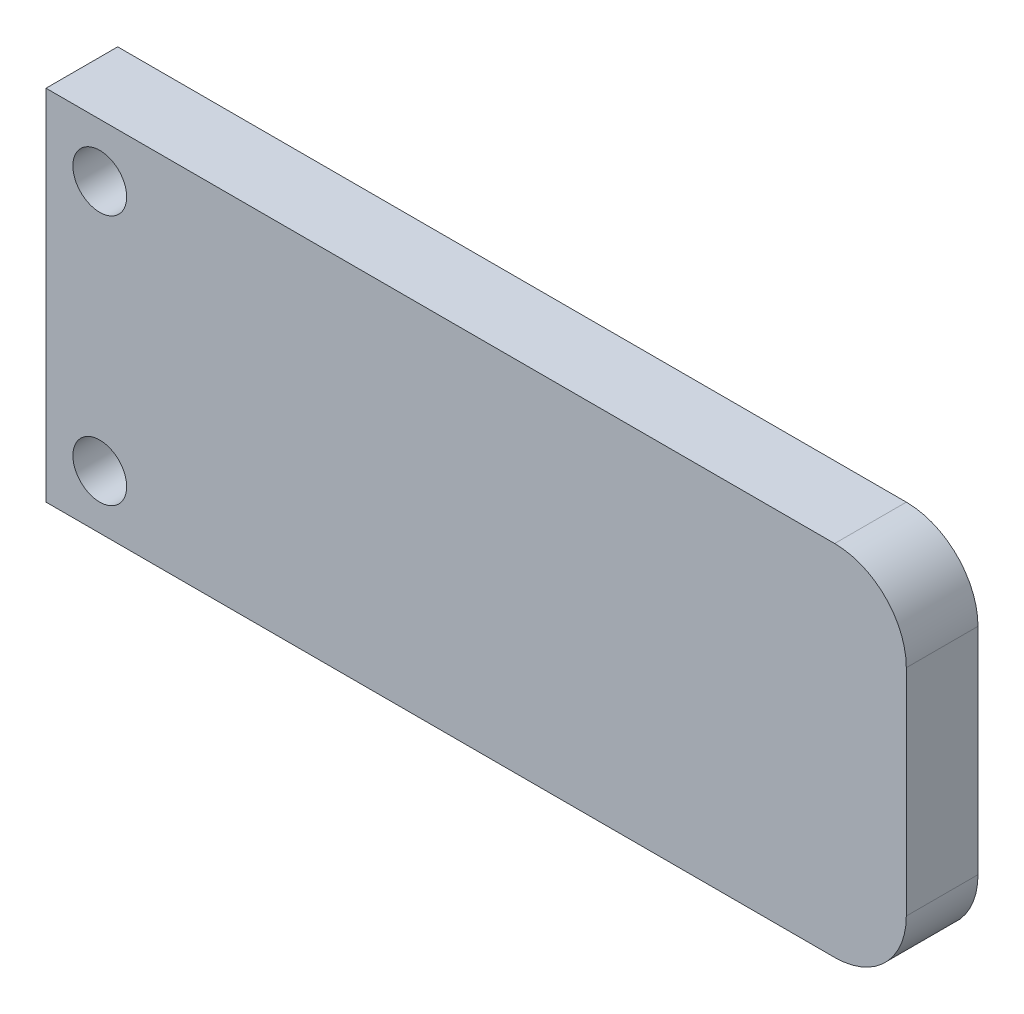
SolidWorks part; units mm, degrees
ref_plane "Plano frontal" through (0, 0, 0) normal (0, 0, 1) x (1, 0, 0)
ref_plane "Plano superior" through (0, 0, 0) normal (0, 1, 0) x (1, 0, 0)
ref_plane "Plano direito" through (0, 0, 0) normal (1, 0, 0) x (0, 0, -1)
sketch "Sketch1" plane through (0, 0, 0) normal (0, 0, 1) x (1, 0, 0)
  line L1 (-24, -10) -> (24, -10)
  line L2 (-24, -10) -> (-24, 10)
  line L3 (-24, 10) -> (24, 10)
  line L4 (24, -10) -> (24, 10)
  line L5 (-24, -10) -> (24, 10) construction
  line L6 (-24, 10) -> (24, -10) construction
  point P0 (0, 0)
  dimension "D1" = 48
  dimension "D2" = 20
extrude "Boss-Extrude1" add sketch "Sketch1" along normal mid plane 4
fillet "Fillet2" radius 4 2 edges at (24, -10, 0) (24, 10, 0)
sketch "Sketch4" plane through (0, 0, -2) normal (0, 0, -1) x (-1, 0, 0)
  line L0 (24, 10) -> (24, -10) construction
  line L1 (-20, 10) -> (24, 10) construction
  line L2 (24, -10) -> (-20, -10) construction
  circle A0 centre (21, 7) radius 1.5
  circle A1 centre (21, -7) radius 1.5
  dimension "D5" = 3
  dimension "D6" = 3
  dimension "D1" = 3
  dimension "D2" = 3
  dimension "D3" = 3
  dimension "D4" = 3
extrude "Cut-Extrude1" cut sketch "Sketch4" against normal up to next
sketch "Sketch3" plane through (0, 0, -2) normal (0, 0, 1) x (1, 0, 0)
  line L1 (13.75, 0) -> (19.25, 0)
  circle A0 centre (16.5, 0) radius 2.75
  dimension "D1" = 5.5
  dimension "D2" = 37.5
revolve "Cut-Revolve1" cut sketch "Sketch3" angle 180 about L1
equation "\"D3@Sketch4\"=\"D2@Sketch4\""
equation "\"D4@Sketch4\"=\"D1@Sketch4\""
equation "\"D6@Sketch4\"=\"D5@Sketch4\""
